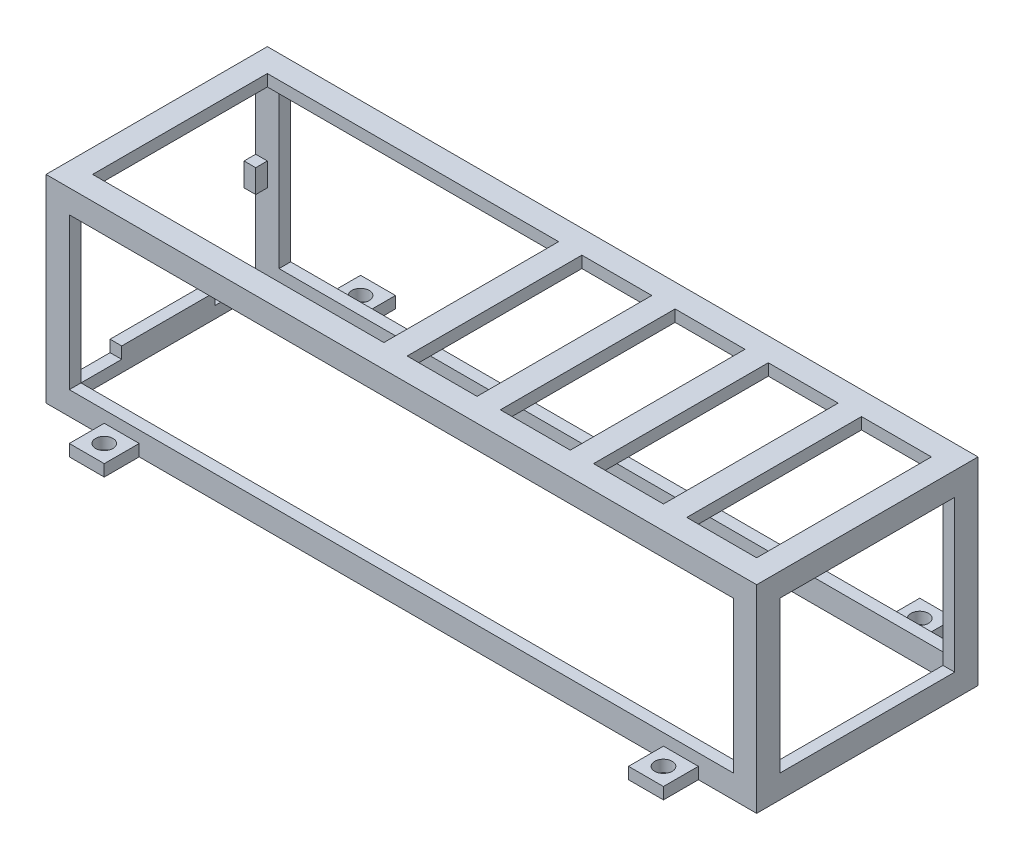
SolidWorks part; units mm, degrees
ref_plane "Front Plane" through (0, 0, 0) normal (0, 0, 1) x (1, 0, 0)
ref_plane "Top Plane" through (0, 0, 0) normal (0, 1, 0) x (1, 0, 0)
ref_plane "Right Plane" through (0, 0, 0) normal (1, 0, 0) x (0, 0, -1)
sketch "Sketch1" plane through (0, 0, 0) normal (0, 1, 0) x (1, 0, 0)
  line L1 (0, 0) -> (122, 0)
  line L2 (0, 0) -> (0, 38)
  line L3 (0, 38) -> (122, 38)
  line L4 (122, 0) -> (122, 38)
  line L5 (2, 2) -> (120, 2)
  line L6 (2, 2) -> (2, 36)
  line L7 (2, 36) -> (120, 36)
  line L8 (120, 2) -> (120, 36)
  dimension "D1" = 122
  dimension "D2" = 38
extrude "Boss-Extrude1" add sketch "Sketch1" along normal blind 34
sketch "Sketch2" plane through (0, 0, 0) normal (-1, 0, 0) x (0, 0, 1)
  line L0 (-38, 34) -> (0, 34) construction
  line L1 (-2, 32) -> (-36, 32)
  line L2 (-2, 32) -> (-2, 34)
  line L3 (-2, 34) -> (-36, 34)
  line L4 (-36, 32) -> (-36, 34)
extrude "Boss-Extrude2" add sketch "Sketch2" against normal blind 120
sketch "Sketch3" plane through (0, 0, 0) normal (-1, 0, 0) x (0, 0, 1)
  line L2 (-8, 2) -> (-2, 2)
  line L3 (-2, 2) -> (-2, 15)
  line L4 (-2, 32) -> (-11, 32)
  line L5 (-36, 32) -> (-36, 19)
  line L6 (-36, 2) -> (-30, 2)
  line L9 (-2, 19) -> (-2, 32)
  line L10 (-2, 15) -> (-4, 15)
  line L11 (-4, 15) -> (-4, 19)
  line L12 (-4, 19) -> (-2, 19)
  line L13 (-36, 15) -> (-34, 15)
  line L14 (-34, 15) -> (-34, 19)
  line L15 (-34, 19) -> (-36, 19)
  line L16 (-36, 15) -> (-36, 2)
  line L17 (-8, 2) -> (-11, 2)
  line L18 (-11, 32) -> (-11, 30)
  line L19 (-11, 30) -> (-27, 30)
  line L20 (-27, 30) -> (-27, 32)
  line L21 (-27, 32) -> (-36, 32)
  line L22 (-11, 2) -> (-11, 4)
  line L23 (-11, 4) -> (-27, 4)
  line L24 (-27, 4) -> (-27, 2)
  line L25 (-27, 2) -> (-30, 2)
  dimension "D1" = 16
  dimension "D2" = 2
  dimension "D3" = 16
  dimension "D4" = 4
  dimension "D5" = 2
  dimension "D6" = 4
  dimension "D7" = 2
  dimension "D8" = 2
extrude "Cut-Extrude2" cut sketch "Sketch3" against normal blind 2
sketch "Sketch4" plane through (0, 0, -38) normal (0, 0, -1) x (-1, 0, 0)
  line L0 (-61, -1000) -> (-61, 49000) construction
  line L1 (-122, 0) -> (0, 0) construction
  line L2 (-1000, 17) -> (49000, 17) construction
  line L3 (0, 34) -> (0, 0) construction
  line L5 (-4, 4) -> (-118, 4)
  line L6 (-4, 4) -> (-4, 30)
  line L7 (-4, 30) -> (-118, 30)
  line L8 (-118, 4) -> (-118, 30)
  point P5 (-61, 0)
  point P10 (0, 17)
  dimension "D1" = 114
  dimension "D2" = 26
extrude "Cut-Extrude4" cut sketch "Sketch4" against normal blind 2
sketch "Sketch6" plane through (0, 0, 0) normal (0, 0, 1) x (1, 0, 0)
  line L0 (61, -966) -> (61, 49034) construction
  line L1 (0, 34) -> (122, 34) construction
  line L2 (-878, 17) -> (49122, 17) construction
  line L3 (122, 34) -> (122, 0) construction
  line L5 (118, 4) -> (4, 4)
  line L6 (118, 4) -> (118, 30)
  line L7 (118, 30) -> (4, 30)
  line L8 (4, 4) -> (4, 30)
  point P5 (61, 34)
  point P10 (122, 17)
  dimension "D1" = 114
  dimension "D2" = 26
extrude "Cut-Extrude5" cut sketch "Sketch6" against normal blind 2
sketch "Sketch7" plane through (122, 0, 0) normal (1, 0, 0) x (0, 0, -1)
  line L0 (19, -1000) -> (19, 49000) construction
  line L1 (0, 0) -> (38, 0) construction
  line L2 (-962, 17) -> (49038, 17) construction
  line L3 (38, 34) -> (38, 0) construction
  line L4 (4, 30) -> (4, 4)
  line L5 (4, 4) -> (34, 4)
  line L6 (34, 4) -> (34, 30)
  line L7 (34, 30) -> (4, 30)
  point P5 (19, 0)
  point P10 (38, 17)
  dimension "D1" = 30
  dimension "D2" = 26
extrude "Cut-Extrude6" cut sketch "Sketch7" against normal blind 2
sketch "Sketch8" plane through (0, 34, 0) normal (0, 1, 0) x (1, 0, 0)
  line L1 (118, 34) -> (106, 34)
  line L2 (118, 34) -> (118, 4)
  line L3 (118, 4) -> (106, 4)
  line L4 (106, 34) -> (106, 4)
extrude "Cut-Extrude7" cut sketch "Sketch8" against normal blind 2
pattern_linear "LPattern1" count 4 spacing 16 along (-1, 0, 0) of "Cut-Extrude7"
sketch "Sketch9" plane through (0, 34, 0) normal (0, 1, 0) x (1, 0, 0)
  line L0 (54, 34) -> (54, 4)
  line L1 (54, 4) -> (4, 4)
  line L2 (4, 4) -> (4, 34)
  line L3 (4, 34) -> (54, 34)
extrude "Cut-Extrude8" cut sketch "Sketch9" against normal blind 2
sketch "Sketch10" plane through (0, 0, -38) normal (0, 0, -1) x (-1, 0, 0)
  line L0 (-122, 0) -> (0, 0) construction
  line L1 (-10, 0) -> (-16, 0)
  line L2 (-10, 0) -> (-10, 2)
  line L3 (-10, 2) -> (-16, 2)
  line L4 (-16, 0) -> (-16, 2)
extrude "Boss-Extrude5" add sketch "Sketch10" along normal blind 6
sketch "Sketch11" plane through (0, 0, -38) normal (0, 0, -1) x (-1, 0, 0)
  line L0 (-122, 0) -> (-16, 0) construction
  line L1 (-112, 2) -> (-106, 2)
  line L2 (-112, 2) -> (-112, 0)
  line L3 (-112, 0) -> (-106, 0)
  line L4 (-106, 2) -> (-106, 0)
extrude "Boss-Extrude6" add sketch "Sketch11" along normal blind 6
sketch "Sketch12" plane through (0, 0, 0) normal (0, 0, 1) x (1, 0, 0)
  line L1 (0, 0) -> (122, 0) construction
  line L3 (10, 0) -> (16, 0)
  line L4 (10, 0) -> (10, 2)
  line L5 (10, 2) -> (16, 2)
  line L6 (16, 0) -> (16, 2)
extrude "Boss-Extrude7" add sketch "Sketch12" along normal blind 6
sketch "Sketch13" plane through (0, 0, 0) normal (0, 0, 1) x (1, 0, 0)
  line L1 (16, 0) -> (122, 0) construction
  line L3 (112, 0) -> (106, 0)
  line L4 (112, 0) -> (112, 2)
  line L5 (112, 2) -> (106, 2)
  line L6 (106, 0) -> (106, 2)
extrude "Boss-Extrude8" add sketch "Sketch13" along normal blind 6
sketch "Sketch14" plane through (0, 0, 0) normal (0, -1, 0) x (1, 0, 0)
  line L0 (-878, -19) -> (49122, -19) construction
  line L1 (122, 0) -> (122, -38) construction
  line L2 (61, -1036) -> (61, 48964) construction
  line L3 (120, -36) -> (2, -36) construction
  circle A0 centre (109, -41) radius 1.5
  circle A1 centre (109, 3) radius 1.5
  circle A2 centre (13, 3) radius 1.5
  circle A3 centre (13, -41) radius 1.5
  point P5 (122, -19)
  point P10 (61, -36)
  point P13 (0, 0)
  point P16 (0, 0)
  point P20 (0, 0)
  dimension "D1" = 3
extrude "Cut-Extrude9" cut sketch "Sketch14" against normal blind 2
